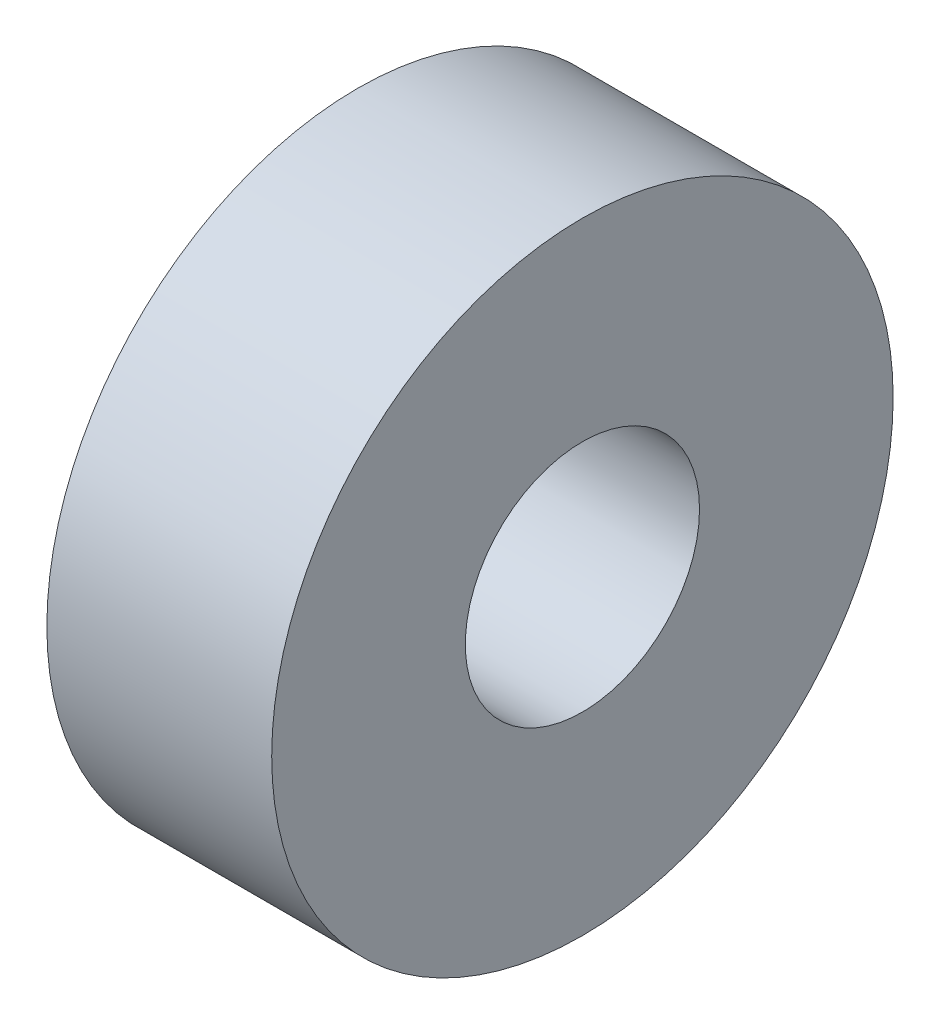
SolidWorks part; units mm, degrees
ref_plane "Front Plane" through (0, 0, 0) normal (0, 0, 1) x (1, 0, 0)
ref_plane "Top Plane" through (0, 0, 0) normal (0, 1, 0) x (1, 0, 0)
ref_plane "Right Plane" through (0, 0, 0) normal (1, 0, 0) x (0, 0, -1)
sketch "Sketch1" plane through (0, 0, 0) normal (1, 0, 0) x (0, 0, -1)
  circle A0 centre (-30.6481, 14.7911) radius 12.6365
  dimension "D1" = 25.273
extrude "Boss-Extrude1" add sketch "Sketch1" along normal blind 9.144
sketch "Sketch2" plane through (9.144, 0, 0) normal (1, 0, 0) x (0, 0, -1)
  circle A0 centre (-30.6481, 14.7911) radius 4.7625
  dimension "D1" = 9.525
extrude "Cut-Extrude1" cut sketch "Sketch2" against normal blind 9.144
